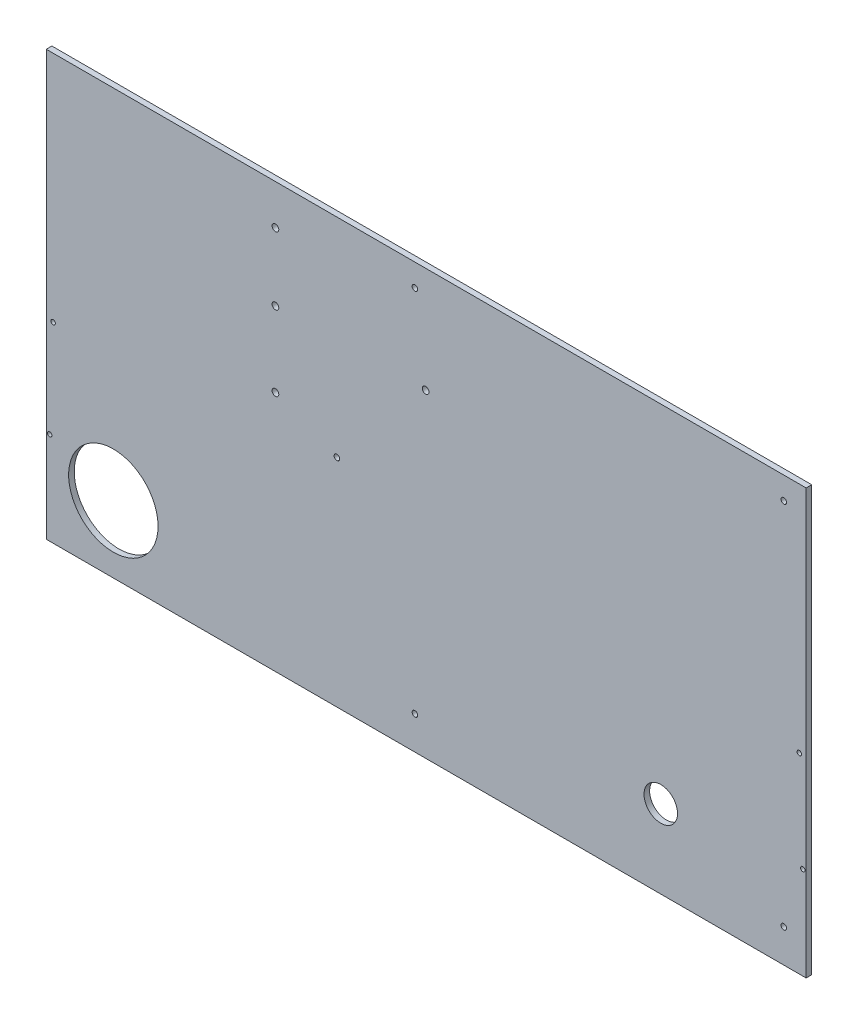
SolidWorks part; units mm, degrees
material "PE High Density"
ref_plane "Front Plane" through (0, 0, 0) normal (0, 0, 1) x (1, 0, 0)
ref_plane "Top Plane" through (0, 0, 0) normal (0, 1, 0) x (1, 0, 0)
ref_plane "Right Plane" through (0, 0, 0) normal (1, 0, 0) x (0, 0, -1)
sketch "Sketch1" plane through (0, 0, 0) normal (0, 0, 1) x (1, 0, 0)
  line L0 (0, 241.1095) -> (0, -241.1095) construction
  line L1 (-431.673, -241.1095) -> (431.673, -241.1095)
  line L2 (-431.673, -241.1095) -> (-431.673, 241.1095)
  line L3 (-431.673, 241.1095) -> (431.673, 241.1095)
  line L4 (431.673, -241.1095) -> (431.673, 241.1095)
  line L5 (-431.673, -241.1095) -> (431.673, 241.1095) construction
  line L6 (-431.673, 241.1095) -> (431.673, -241.1095) construction
  circle A2 centre (-423.9189, -23.5614) radius 2.54
  circle A3 centre (-427.8476, -135.8909) radius 2.54
  circle A8 centre (427.8476, -135.8909) radius 2.54
  circle A9 centre (423.9189, -23.5614) radius 2.54
  point P0 (0, 0)
  dimension "D3" = 3.9287
  dimension "D4" = 112.3295
  dimension "D5" = 5.08
  dimension "D6" = 105.2186
  dimension "D1" = 863.346
  dimension "D2" = 482.219
  dimension "D7" = 847.8378
extrude "Boss-Extrude1" add sketch "Sketch1" along normal blind 6.35
sketch "Sketch2" plane through (0, 0, 6.35) normal (0, 0, 1) x (1, 0, 0)
  line L0 (431.673, -241.1095) -> (431.673, 241.1095) construction
  line L1 (-431.673, -241.1095) -> (431.673, -241.1095) construction
  circle A0 centre (266.5286, -152.3441) radius 19.05
  dimension "D1" = 38.1
  dimension "D2" = 165.1444
  dimension "D3" = 88.7654
extrude "Cut-Extrude1" cut sketch "Sketch2" against normal through all
sketch "Sketch3" plane through (0, 0, 0) normal (0, 0, -1) x (-1, 0, 0)
  line L0 (431.673, 241.1095) -> (431.673, -241.1095) construction
  line L1 (-431.673, 241.1095) -> (431.673, 241.1095) construction
  circle A0 centre (171.2997, 195.6284) radius 3.81
  circle A1 centre (171.2997, 118.6388) radius 3.81
  circle A2 centre (171.2997, 33.5325) radius 3.81
  circle A3 centre (0.6117, 121.0722) radius 3.81
  dimension "D7" = 7.62
  dimension "D1" = 76.9897
  dimension "D2" = 85.1062
  dimension "D3" = 74.5562
  dimension "D4" = 170.688
  dimension "D5" = 260.3733
  dimension "D6" = 45.4811
extrude "Cut-Extrude2" cut sketch "Sketch3" against normal through all
sketch "Sketch4" plane through (0, 0, 6.35) normal (0, 0, 1) x (1, 0, 0)
  line L0 (-431.673, -241.1095) -> (431.673, -241.1095) construction
  line L1 (431.673, -241.1095) -> (431.673, 241.1095) construction
  circle A0 centre (-12.827, 215.7095) radius 3.175
  circle A1 centre (-12.827, -203.3905) radius 3.175
  circle A2 centre (406.273, -203.3905) radius 3.175
  circle A3 centre (406.273, 215.7095) radius 3.175
  dimension "D5" = 6.35
  dimension "D1" = 37.719
  dimension "D2" = 25.4
  dimension "D3" = 419.1
  dimension "D4" = 419.1
extrude "Cut-Extrude3" cut sketch "Sketch4" against normal through all
sketch "Sketch5" plane through (0, 0, 6.35) normal (0, 0, 1) x (1, 0, 0)
  line L6 (-431.673, -241.1095) -> (431.673, -241.1095) construction
  line L7 (-431.673, 241.1095) -> (-431.673, -241.1095) construction
  circle A0 centre (-355.473, -164.9095) radius 50.8
  dimension "D1" = 101.6
  dimension "D2" = 76.2
  dimension "D3" = 76.2
extrude "Cut-Extrude4" cut sketch "Sketch5" against normal through all
sketch "Sketch6" plane through (0, 0, 6.35) normal (0, 0, 1) x (1, 0, 0)
  line L0 (-431.673, 241.1095) -> (-431.673, -241.1095) construction
  line L1 (431.673, 241.1095) -> (-431.673, 241.1095) construction
  circle A0 centre (-101.473, 4.6355) radius 3.175
  dimension "D3" = 6.35
  dimension "D1" = 330.2
  dimension "D2" = 236.474
extrude "Cut-Extrude5" cut sketch "Sketch6" against normal through all
